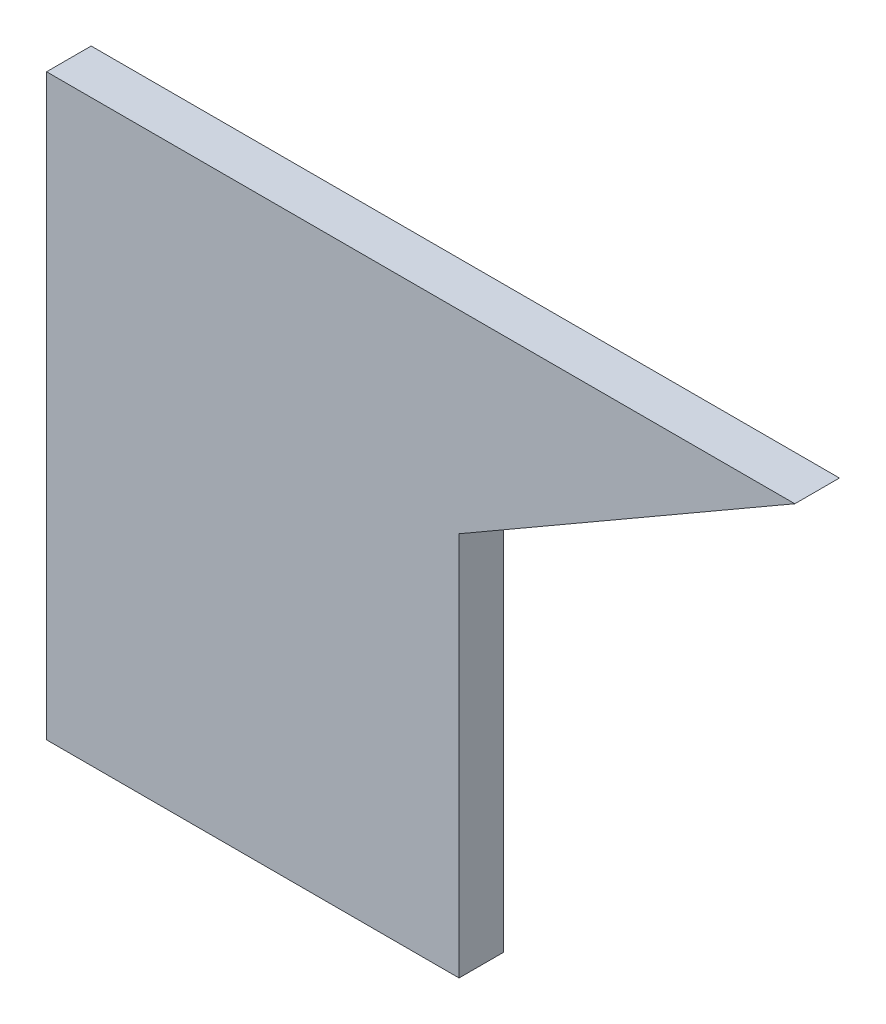
SolidWorks part; units mm, degrees
material "Oak"
ref_plane "Front Plane" through (0, 0, 0) normal (0, 0, 1) x (1, 0, 0)
ref_plane "Top Plane" through (0, 0, 0) normal (0, 1, 0) x (1, 0, 0)
ref_plane "Right Plane" through (0, 0, 0) normal (1, 0, 0) x (0, 0, -1)
sketch "Sketch1" plane through (0, 0, 0) normal (0, 0, 1) x (1, 0, 0)
  line L0 (58.7375, 27.1776) -> (154.3704, 82.3912)
  line L1 (-58.7375, -82.3913) -> (58.7375, -82.3912)
  line L2 (-58.7375, -82.3913) -> (-58.7375, 82.3912)
  line L3 (-58.7375, 82.3912) -> (154.3704, 82.3912)
  line L4 (58.7375, -82.3912) -> (58.7375, 27.1776)
  line L5 (-58.7375, -82.3913) -> (58.7375, 82.3912) construction
  line L6 (-58.7375, 82.3912) -> (58.7375, -82.3912) construction
  line L7 (273.737, 82.3913) -> (179.757, 82.3913) construction
  point P0 (0, 0)
  point P10 (0, 0)
  point P11 (148.7673, 82.3912)
  dimension "D1" = 164.7825
  dimension "D2" = 117.475
  dimension "D3" = 30
  dimension "D4" = 213.1079
extrude "Boss-Extrude1" add sketch "Sketch1" along normal mid plane 12.7
